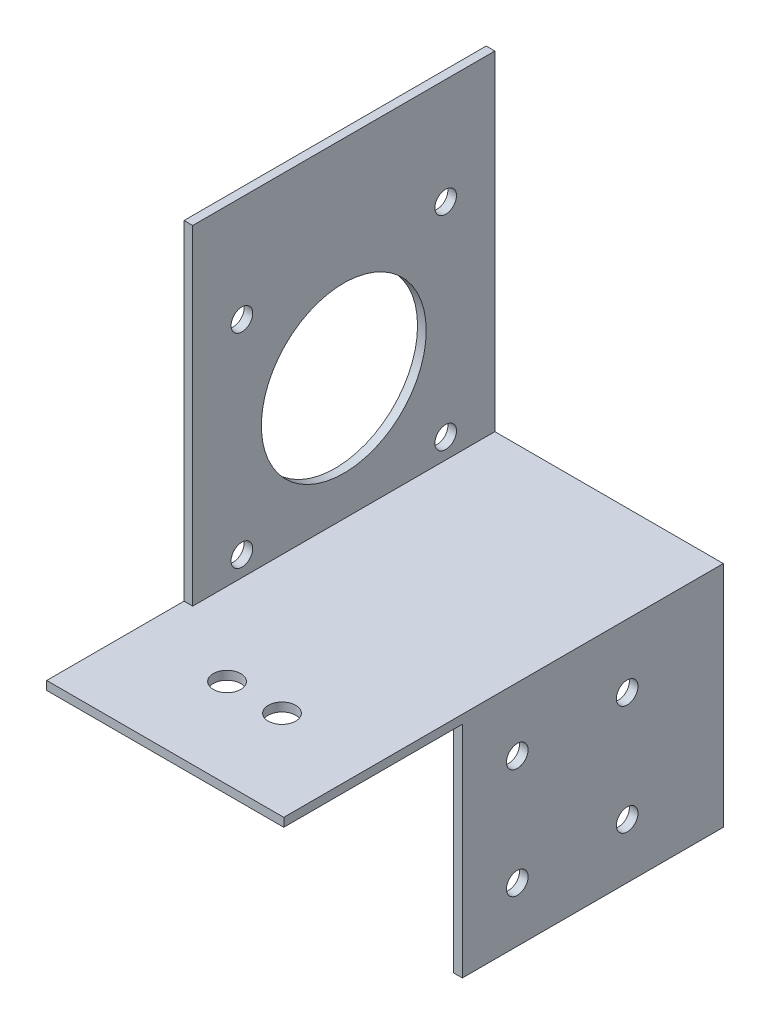
SolidWorks part; units mm, degrees
ref_plane "Front Plane" through (0, 0, 0) normal (0, 0, 1) x (1, 0, 0)
ref_plane "Top Plane" through (0, 0, 0) normal (0, 1, 0) x (1, 0, 0)
ref_plane "Right Plane" through (0, 0, 0) normal (1, 0, 0) x (0, 0, -1)
sketch "Sketch1" plane through (0, 0, 0) normal (1, 0, 0) x (0, 0, -1)
  line L1 (-34.925, -25.4) -> (34.925, -25.4)
  line L2 (-34.925, -25.4) -> (-34.925, 25.4)
  line L3 (-34.925, 25.4) -> (34.925, 25.4)
  line L4 (34.925, -25.4) -> (34.925, 25.4)
  line L5 (-34.925, -25.4) -> (34.925, 25.4) construction
  line L6 (-34.925, 25.4) -> (34.925, -25.4) construction
  point P0 (0, 0)
  dimension "D1" = 69.85
  dimension "D2" = 50.8
extrude "Boss-Extrude1" add sketch "Sketch1" against normal blind 2
sketch "Sketch2" plane through (0, 25.4, 0) normal (0, 1, 0) x (1, 0, 0)
  line L0 (-2, -34.925) -> (0, -34.925) construction
  line L1 (0, 34.925) -> (-54.8, 34.925)
  line L2 (0, 34.925) -> (0, -34.925)
  line L3 (0, -34.925) -> (-54.8, -34.925)
  line L4 (-54.8, 34.925) -> (-54.8, -34.925)
  point P7 (-1, -34.925)
  dimension "D1" = 54.8
extrude "Boss-Extrude2" add sketch "Sketch2" along normal blind 2
sketch "Sketch3" plane through (0, 27.4, 0) normal (0, 1, 0) x (1, 0, 0)
  line L0 (-54.8, -34.925) -> (0, -34.925) construction
  line L1 (-54.8, 34.925) -> (-52.8, 34.925)
  line L2 (-54.8, 34.925) -> (-54.8, -34.925)
  line L3 (-54.8, -34.925) -> (-52.8, -34.925)
  line L4 (-52.8, 34.925) -> (-52.8, -34.925)
  dimension "D1" = 2
extrude "Boss-Extrude3" add sketch "Sketch3" along normal blind 76.2
sketch "Sketch4" plane through (-52.8, 0, 0) normal (1, 0, 0) x (0, 0, -1)
  line L1 (-34.925, 27.4) -> (34.925, 27.4) construction
  line L2 (-23.55, 79.118) -> (23.55, 79.118) construction
  line L3 (23.55, 79.118) -> (23.55, 32.018) construction
  line L4 (23.55, 32.018) -> (-23.55, 32.018) construction
  line L5 (-23.55, 32.018) -> (-23.55, 79.118) construction
  line L6 (0, 55.568) -> (0, 103.6) construction
  line L7 (-34.925, 103.6) -> (34.925, 103.6) construction
  circle A0 centre (0, 55.568) radius 19.05
  circle A1 centre (23.55, 79.118) radius 2.5
  circle A2 centre (-23.55, 79.118) radius 2.5
  circle A3 centre (-23.55, 32.018) radius 2.5
  circle A4 centre (23.55, 32.018) radius 2.5
  dimension "D3" = 38.1
  dimension "D8" = 5
  dimension "D2" = 28.168
  dimension "D4" = 23.55
  dimension "D5" = 23.55
  dimension "D6" = 23.55
  dimension "D7" = 23.55
extrude "Cut-Extrude1" cut sketch "Sketch4" against normal through all
sketch "Sketch5" plane through (0, 0, 0) normal (1, 0, 0) x (0, 0, -1)
  line L0 (-34.925, -25.4) -> (34.925, -25.4) construction
  line L1 (-34.925, 27.4) -> (-25.4, 27.4)
  line L2 (-34.925, 27.4) -> (-34.925, -25.4)
  line L3 (-34.925, -25.4) -> (-25.4, -25.4)
  line L4 (-25.4, 27.4) -> (-25.4, -25.4)
  line L5 (-12.7, 12.7) -> (12.7, 12.7) construction
  line L6 (12.7, 12.7) -> (12.7, -12.7) construction
  line L7 (12.7, -12.7) -> (-12.7, -12.7) construction
  line L8 (-12.7, -12.7) -> (-12.7, 12.7) construction
  circle A0 centre (-12.7, 12.7) radius 2.5
  circle A1 centre (12.7, 12.7) radius 2.5
  circle A2 centre (12.7, -12.7) radius 2.5
  circle A3 centre (-12.7, -12.7) radius 2.5
  dimension "D6" = 5
  dimension "D1" = 25.4
  dimension "D2" = 12.7
  dimension "D3" = 12.7
  dimension "D4" = 12.7
  dimension "D5" = 12.7
extrude "Cut-Extrude2" cut sketch "Sketch5" against normal through all
sketch "Sketch6" plane through (0, 0, 25.4) normal (0, 0, 1) x (1, 0, 0)
  line L1 (0, 27.4) -> (-54.8, 27.4)
  line L2 (0, 27.4) -> (0, 25.4)
  line L3 (0, 25.4) -> (-54.8, 25.4)
  line L4 (-54.8, 27.4) -> (-54.8, 25.4)
extrude "Boss-Extrude4" add sketch "Sketch6" along normal blind 41.275
sketch "Sketch7" plane through (0, 27.4, 0) normal (0, 1, 0) x (1, 0, 0)
  line L0 (-54.8, -66.675) -> (0, -66.675) construction
  line L1 (-21.05, -46.0375) -> (-33.75, -46.0375) construction
  line L2 (-27.4, -66.675) -> (-27.4, -46.0375) construction
  circle A0 centre (-33.75, -46.0375) radius 3.175
  circle A1 centre (-21.05, -46.0375) radius 3.175
  point P6 (-27.4, -46.0375)
  point P7 (-27.4, -66.675)
  dimension "D1" = 6.35
  dimension "D2" = 20.6375
  dimension "D3" = 6.35
extrude "Cut-Extrude3" cut sketch "Sketch7" against normal through all
